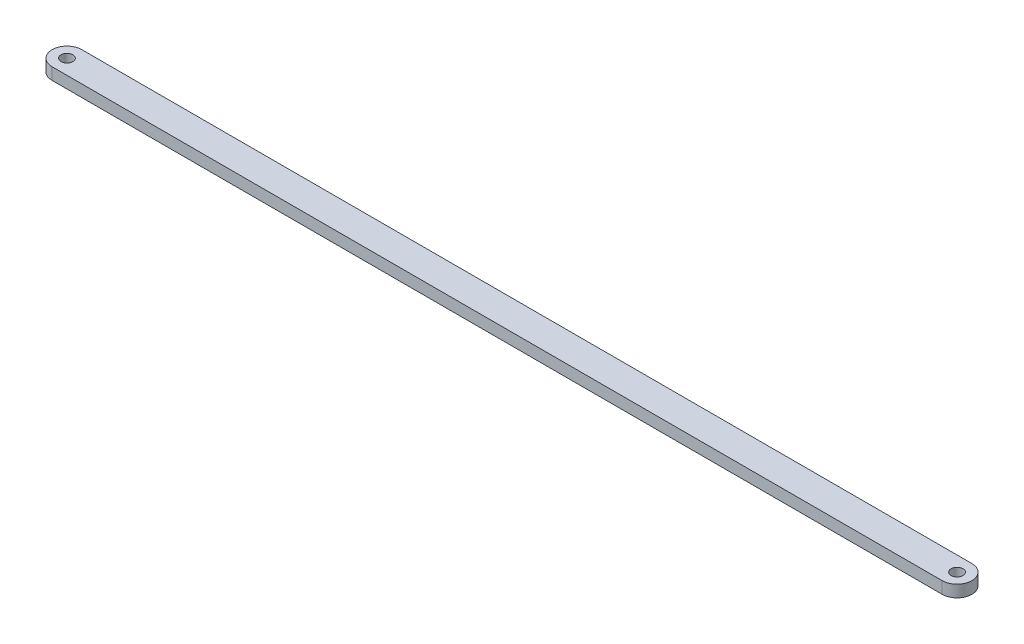
SolidWorks part; units mm, degrees
ref_plane "Front Plane" through (0, 0, 0) normal (0, 0, 1) x (1, 0, 0)
ref_plane "Top Plane" through (0, 0, 0) normal (0, 1, 0) x (1, 0, 0)
ref_plane "Right Plane" through (0, 0, 0) normal (1, 0, 0) x (0, 0, -1)
sketch "Sketch1" plane through (0, 0, 0) normal (0, 1, 0) x (1, 0, 0)
  line L0 (-10, 0) -> (140, 0) construction
  line L1 (-10, 2.5) -> (140, 2.5)
  line L2 (-10, -2.5) -> (140, -2.5)
  arc A0 (-10, 2.5) -> (-10, -2.5) centre (-10, 0) ccw
  arc A1 (140, -2.5) -> (140, 2.5) centre (140, 0) ccw
  circle A2 centre (140, 0) radius 1
  circle A3 centre (-10, 0) radius 1
  point P3 (65, 0)
  dimension "D3" = 2
  dimension "D4" = 2.5
  dimension "D5" = 2
  dimension "D1" = 150
  dimension "D12" = 10
extrude "Boss-Extrude1" add sketch "Sketch1" along normal blind 2
